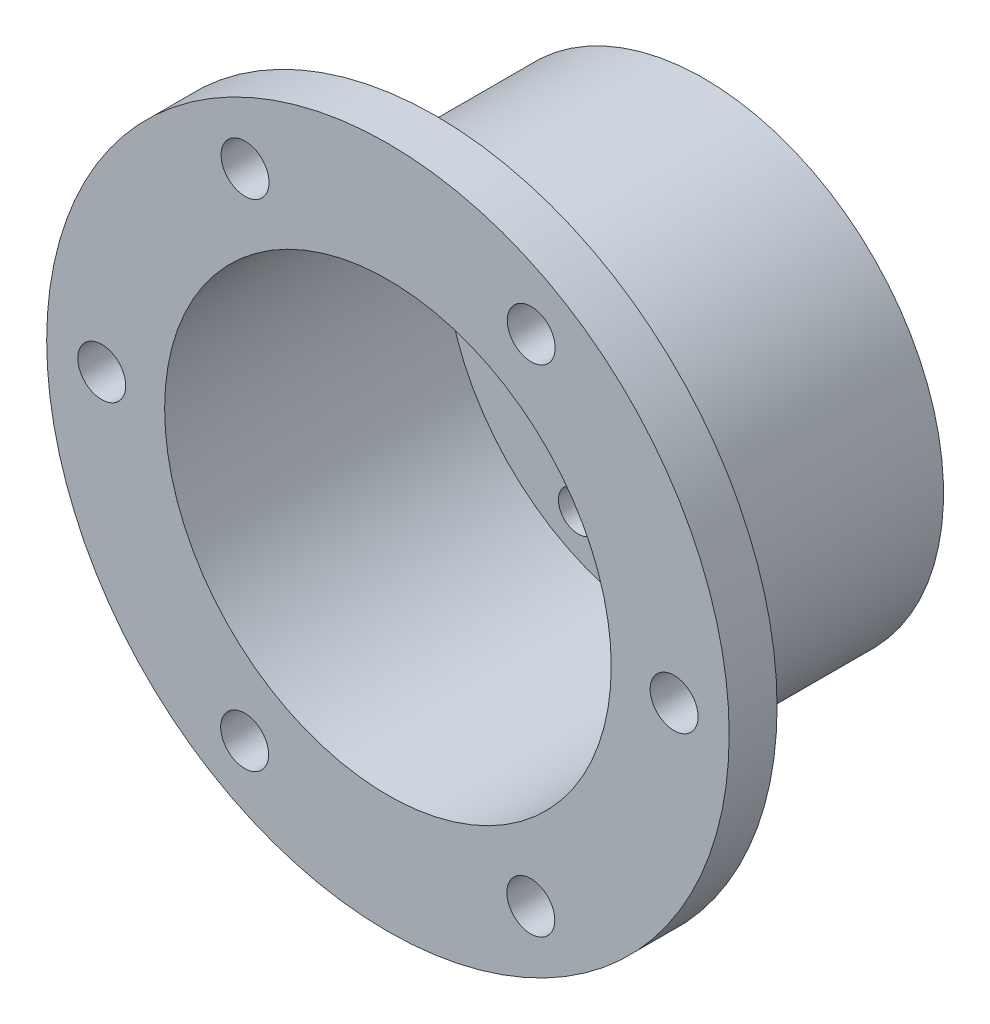
SolidWorks part; units mm, degrees
material "Resina de melamina"
ref_plane "Alzado" through (0, 0, 0) normal (0, 0, 1) x (1, 0, 0)
ref_plane "Planta" through (0, 0, 0) normal (0, 1, 0) x (1, 0, 0)
ref_plane "Vista lateral" through (0, 0, 0) normal (1, 0, 0) x (0, 0, -1)
sketch "Croquis1" plane through (0, 0, 0) normal (0, 0, 1) x (1, 0, 0)
  circle A0 centre (0, 0) radius 18.65
  circle A1 centre (0, 0) radius 21.4
  dimension "D1" = 37.3
  dimension "D2" = 42.8
extrude "Saliente-Extruir1" add sketch "Croquis1" along normal blind 26.4
sketch "Croquis2" plane through (0, 0, 0) normal (0, 0, -1) x (-1, 0, 0)
  circle A0 centre (0, 0) radius 18.65
  dimension "D1" = 37.3
extrude "Saliente-Extruir2" add sketch "Croquis2" against normal blind 3
sketch "Croquis3" plane through (0, 0, 26.4) normal (0, 0, 1) x (1, 0, 0)
  circle A0 centre (0, 0) radius 21.4
  circle A1 centre (0, 0) radius 28.5
  dimension "D1" = 57
extrude "Saliente-Extruir3" add sketch "Croquis3" against normal blind 4
sketch "Croquis4" plane through (0, 0, 0) normal (0, 0, -1) x (-1, 0, 0)
  line L0 (0, 0) -> (0, -7) construction
  line L1 (-12.848, 0.2243) -> (-13.8479, 0.2417) construction
  line L2 (-13.8479, 0.2417) -> (-17.1474, 0.2993) construction
  circle A0 centre (0, -7) radius 6.15
  circle A9 centre (-15.4976, 0.2705) radius 1.65
  circle A10 centre (-7.5145, 13.5566) radius 1.65
  circle A11 centre (7.9831, 13.2861) radius 1.65
  circle A12 centre (15.4976, -0.2705) radius 1.65
  circle A13 centre (7.5145, -13.5566) radius 1.65
  circle A14 centre (-7.9831, -13.2861) radius 1.65
  dimension "D2" = 12.3
  dimension "D6" = 15.5
  dimension "D1" = 7
  dimension "D3" = 1
  dimension "D4" = 3.3
  dimension "D5" = 6
extrude "Cortar-Extruir1" cut sketch "Croquis4" against normal blind 3
sketch "Croquis6" plane through (0, 0, 26.4) normal (0, 0, 1) x (1, 0, 0)
  line L4 (0, 0) -> (23.9, -0.0193) construction
  circle A1 centre (11.9667, 20.6884) radius 2
  circle A8 centre (23.9, -0.0193) radius 2
  circle A10 centre (-11.9333, 20.7077) radius 2
  circle A16 centre (11.9333, -20.7077) radius 2
  circle A17 centre (-11.9667, -20.6884) radius 2
  circle A18 centre (-23.9, 0.0193) radius 2
  dimension "D1" = 23.9
  dimension "D2" = 4
  dimension "D3" = 6
extrude "Cortar-Extruir2" cut sketch "Croquis6" against normal through all
sketch "Croquis7" plane through (0, 0, 0) normal (0, 0, -1) x (-1, 0, 0)
  circle A0 centre (0, 0) radius 20
  circle A1 centre (0, 0) radius 21.4
  dimension "40" = 40
extrude "Cortar-Extruir3" cut sketch "Croquis7" against normal blind 22.4
fillet "Redondeo1" radius 1 1 edges at (-20, 0, 22.4)
